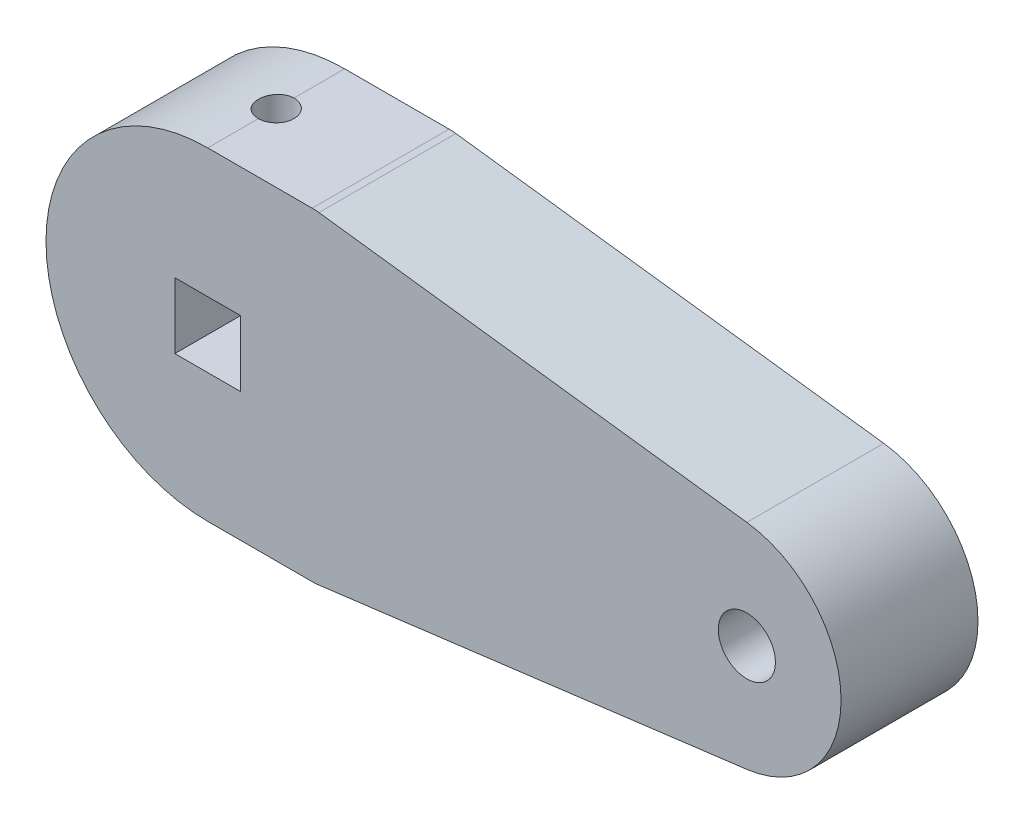
SolidWorks part; units mm, degrees
material "ABS"
ref_plane "Front Plane" through (0, 0, 0) normal (0, 0, 1) x (1, 0, 0)
ref_plane "Top Plane" through (0, 0, 0) normal (0, 1, 0) x (1, 0, 0)
ref_plane "Right Plane" through (0, 0, 0) normal (1, 0, 0) x (0, 0, -1)
sketch "Sketch1" plane through (0, 0, 0) normal (0, 0, 1) x (1, 0, 0)
  line L0 (50, 9.9203) -> (10, 15)
  line L1 (-3.05, 3.05) -> (3.05, 3.05)
  line L2 (-3.05, 3.05) -> (-3.05, -3.05)
  line L3 (-3.05, -3.05) -> (3.05, -3.05)
  line L4 (3.05, 3.05) -> (3.05, -3.05)
  line L5 (10, -15) -> (50, -9.9203)
  line L6 (10, 15) -> (0, 15)
  line L7 (10, -15) -> (0, -15)
  circle A0 centre (50, 0) radius 2.5 construction
  arc A1 (50, 9.9203) -> (50, -9.9203) centre (48.7402, 0) cw
  arc A3 (0, 15) -> (0, -15) centre (0, 0) ccw
  point P6 (3.05, 0)
  point P8 (0, 3.05)
  point P14 (-3.05, 13.9941)
  point P16 (-3.05, 1.0777)
  point P17 (-3.05, 1.3478)
  point P19 (-0.6373, 17.0246)
  point P20 (0, 10.4631)
  point P22 (0, 0)
  dimension "D2" = 5
  dimension "D4" = 10
  dimension "D5" = 10
  dimension "D6" = 15
  dimension "D1" = 6.1
  dimension "D3" = 50
extrude "Boss-Extrude1" add sketch "Sketch1" along normal blind 12.7
sketch "Sketch2" plane through (0, 15, 0) normal (0, 1, 0) x (1, 0, 0)
  line L0 (0, -12.7) -> (0, 0) construction
  circle A0 centre (0, -6.35) radius 2 construction
  dimension "D1" = 4
hole_wizard "Tap Drill for M4x0.7 Tap1" positions "3DSketch1" profile "Sketch3" hole size "M4x0.7" standard "ANSI Metric"
sketch3d "3DSketch1"
  point P0 (0, 15, 6.35)
  point P3 (0, 15, 6.35)
sketch "Sketch3" plane through (0, 15, 6.35) normal (1, 0, 0) x (0, 0, 1)
  line L0 (0, 0) -> (0, 11.95)
  line L1 (0, 11.95) -> (1.65, 11.95)
  line L2 (1.65, 11.95) -> (1.65, 0)
  line L5 (1.65, 0) -> (0, 0)
  line L11 (0, -6.35) -> (0, 107.95) construction
  dimension "Thru Hole Dia." = 3.3
  dimension "Thru Hole Depth" = 11.95
hole_wizard "M5 Clearance Hole1" positions "3DSketch2" profile "Sketch4" hole size "M5" standard "ANSI Metric" end condition up to next
sketch3d "3DSketch2"
  point P0 (50, 0, 0)
  point P3 (50, 0, 0)
sketch "Sketch4" plane through (50, 0, 0) normal (1, 0, 0) x (0, 1, 0)
  line L0 (0, 0) -> (0, 12.7)
  line L1 (0, 12.7) -> (2.65, 12.7)
  line L2 (2.65, 12.7) -> (2.65, 0)
  line L5 (2.65, 0) -> (0, 0)
  line L11 (0, -6.35) -> (0, 107.95) construction
  dimension "Thru Hole Dia." = 5.3
  dimension "Thru Hole Depth" = 12.7
fillet "Fillet1" radius 5 2 edges at (10, -15, 6.35) (10, 15, 6.35)
